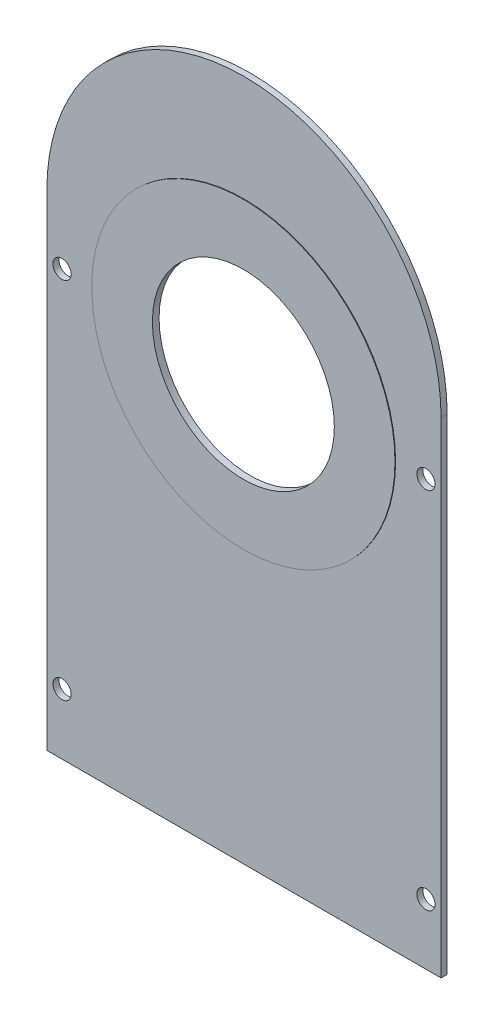
SolidWorks part; units mm, degrees
ref_plane "Front Plane" through (0, 0, 0) normal (0, 0, 1) x (1, 0, 0)
ref_plane "Top Plane" through (0, 0, 0) normal (0, 1, 0) x (1, 0, 0)
ref_plane "Right Plane" through (0, 0, 0) normal (1, 0, 0) x (0, 0, -1)
sketch "Sketch1" plane through (0, 0, 0) normal (0, 0, 1) x (1, 0, 0)
  line L0 (0, -40) -> (0, 72.5) construction
  line L1 (-32.5, 40) -> (32.5, 40)
  line L2 (-32.5, 40) -> (-32.5, -40)
  line L3 (-32.5, -40) -> (32.5, -40)
  line L4 (32.5, 40) -> (32.5, -40)
  line L5 (-32.5, 40) -> (32.5, -40) construction
  line L6 (-32.5, -40) -> (32.5, 40) construction
  line L7 (-32.5, 0) -> (32.5, 0) construction
  line L8 (-30, 30) -> (30, 30) construction
  arc A0 (-32.5, 40) -> (32.5, 40) centre (0, 40) cw
  circle A1 centre (-30, -30) radius 1.5
  circle A2 centre (-30, 30) radius 1.5
  circle A3 centre (30, -30) radius 1.5
  circle A4 centre (30, 30) radius 1.5
  circle A5 centre (0, 30) radius 15
  point P0 (0, 0)
  point P21 (0, 0)
  dimension "D3" = 3
  dimension "D6" = 30
  dimension "D1" = 65
  dimension "D2" = 80
  dimension "D4" = 2.5
  dimension "D5" = 10
extrude "Boss-Extrude1" add sketch "Sketch1" along normal blind 1 contours L4 L1 L2 L3 | A0 L1
sketch "Sketch2" plane through (0, 0, 1) normal (0, 0, 1) x (1, 0, 0)
  circle A0 centre (0, 30) radius 25
  dimension "D1" = 50
extrude "Boss-Extrude2" add sketch "Sketch2" along normal blind 0.1
sketch "Sketch3" plane through (0, 0, 1) normal (0, 0, -1) x (-1, 0, 0)
  circle A0 centre (0, 30) radius 15
  dimension "D1" = 30
extrude "Cut-Extrude1" cut sketch "Sketch3" against normal blind 1
